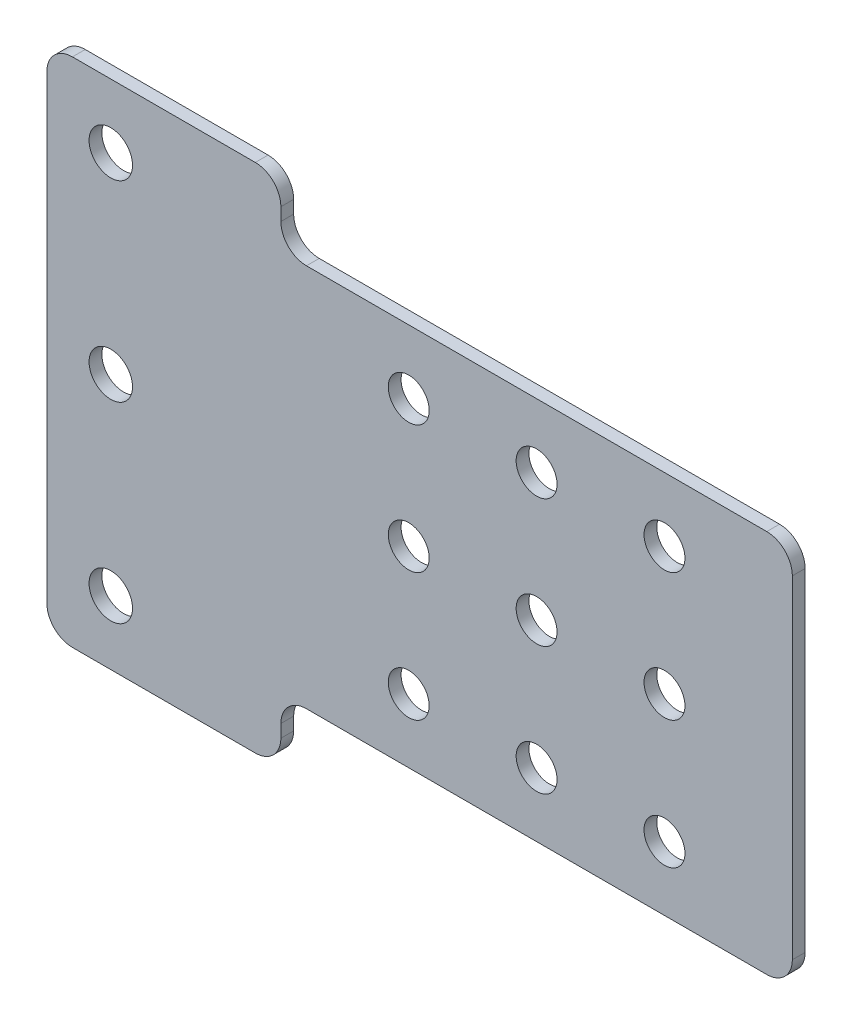
SolidWorks part; units mm, degrees
ref_plane "Front Plane" through (0, 0, 0) normal (0, 0, 1) x (1, 0, 0)
ref_plane "Top Plane" through (0, 0, 0) normal (0, 1, 0) x (1, 0, 0)
ref_plane "Right Plane" through (0, 0, 0) normal (1, 0, 0) x (0, 0, -1)
sketch "Sketch1" plane through (0, 0, 0) normal (0, 0, 1) x (1, 0, 0)
  line L1 (-25.4, -19.05) -> (25.4, -19.05)
  line L2 (-25.4, -19.05) -> (-25.4, 19.05)
  line L3 (-25.4, 19.05) -> (25.4, 19.05)
  line L4 (25.4, -19.05) -> (25.4, 19.05)
  line L5 (-25.4, -19.05) -> (25.4, 19.05) construction
  line L6 (-25.4, 19.05) -> (25.4, -19.05) construction
  circle A0 centre (-12.7, 12.7) radius 2.032
  circle A1 centre (0, 12.7) radius 2.032
  circle A2 centre (12.7, 12.7) radius 2.032
  circle A3 centre (0, 0) radius 2.032
  circle A4 centre (12.7, 0) radius 2.032
  circle A5 centre (0, -12.7) radius 2.032
  circle A6 centre (12.7, -12.7) radius 2.032
  circle A7 centre (-12.7, 0) radius 2.032
  circle A8 centre (-12.7, -12.7) radius 2.032
  point P0 (0, 0)
  dimension "D3" = 4.064
  dimension "D1" = 50.8
  dimension "D2" = 38.1
  dimension "D4" = 6.35
  dimension "D5" = 12.7
  dimension "D6" = 3
  dimension "D7" = 3
extrude "Boss-Extrude1" add sketch "Sketch1" along normal blind 1.27
sketch "Sketch2" plane through (0, 0, 1.27) normal (0, 0, 1) x (1, 0, 0)
  line L0 (-42.291, 0) -> (-42.291, -19.05) construction
  line L2 (-42.291, 0) -> (-42.291, 19.05) construction
  line L3 (-25.4, -19.05) -> (-25.4, -25.4)
  line L4 (-25.4, -25.4) -> (-48.641, -25.4)
  line L5 (-48.641, -25.4) -> (-48.641, 25.4)
  line L6 (-48.641, 25.4) -> (-25.4, 25.4)
  line L7 (-48.641, -25.4) -> (-48.6701, -25.4403)
  line L8 (-25.4, 19.05) -> (-25.4, 25.4)
  line L9 (-25.4, 19.05) -> (-25.4, -19.05) construction
  line L10 (-25.4, -19.05) -> (25.4, -19.05) construction
  line L14 (-12.7, -19.05) -> (-12.1469, -19.05)
  circle A0 centre (-42.291, 0) radius 2.159
  circle A1 centre (-42.291, -19.05) radius 2.159
  circle A2 centre (-42.291, 19.05) radius 2.159
  point P22 (-47.752, -25.4)
  dimension "D1" = 16.891
  dimension "D4" = 6.35
  dimension "D3" = 19.05
  dimension "D6" = 6.35
fillet "Fillet3" radius 2.54 2 edges at (25.4, -19.05, 0.635) (25.4, 19.05, 0.635)
extrude "Boss-Extrude2" add sketch "Sketch2" against normal up to surface (1.27 mm away)
fillet "Fillet6" radius 2.54 6 edges at (-25.4, -19.05, 0.635) (-25.4, -25.4, 0.635) (-48.641, -25.4, 0.635) (-25.4, 19.05, 0.635) (-48.641, 25.4, 0.635) (-25.4, 25.4, 0.635)
